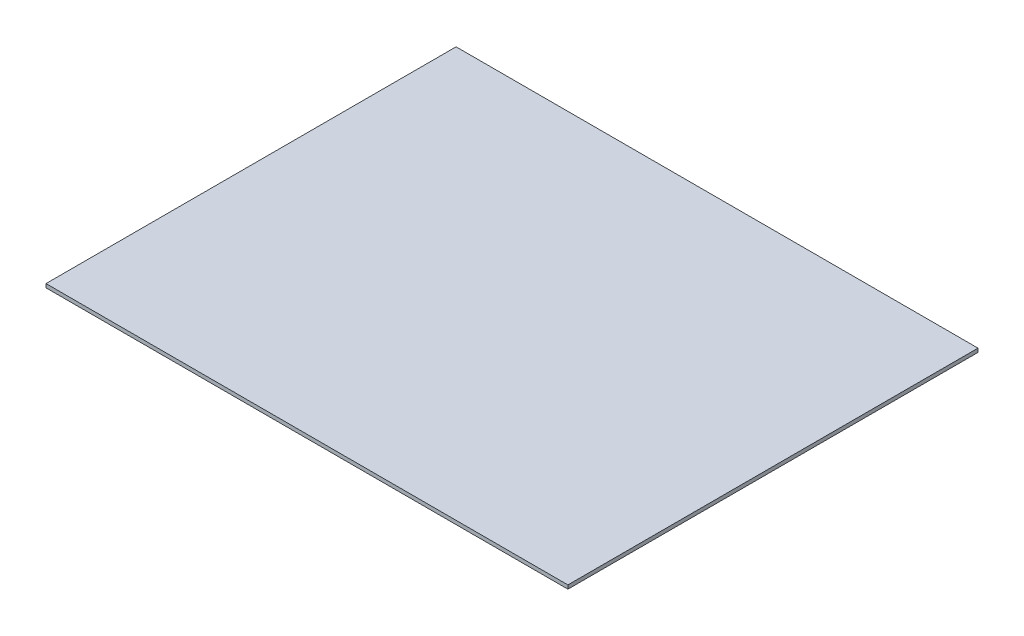
SolidWorks part; units mm, degrees
ref_plane "Front Plane" through (0, 0, 0) normal (0, 0, 1) x (1, 0, 0)
ref_plane "Top Plane" through (0, 0, 0) normal (0, 1, 0) x (1, 0, 0)
ref_plane "Right Plane" through (0, 0, 0) normal (1, 0, 0) x (0, 0, -1)
sketch "Sketch1" plane through (0, 0, 0) normal (0, 1, 0) x (1, 0, 0)
  line L1 (0, 0) -> (-700, 0)
  line L2 (0, 0) -> (0, -550)
  line L3 (0, -550) -> (-700, -550)
  line L4 (-700, 0) -> (-700, -550)
  dimension "D1" = 700
  dimension "D2" = 550
extrude "Boss-Extrude1" add sketch "Sketch1" along normal blind 5
